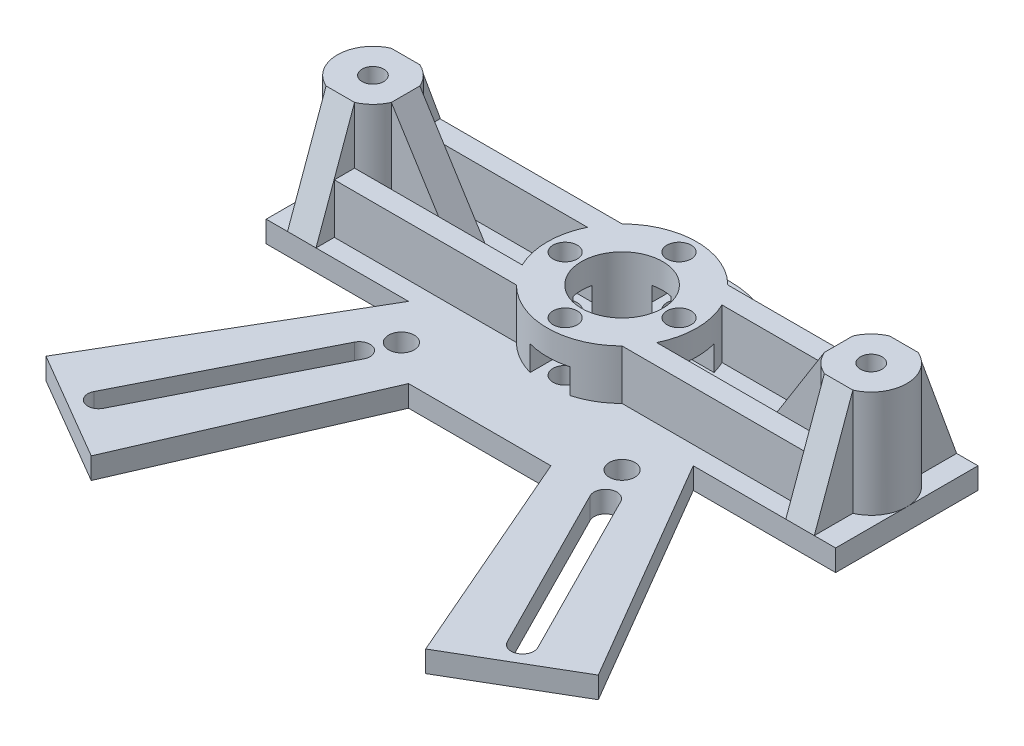
SolidWorks part; units mm, degrees
ref_plane "前视基准面" through (0, 0, 0) normal (0, 0, 1) x (1, 0, 0)
ref_plane "上视基准面" through (0, 0, 0) normal (0, 1, 0) x (1, 0, 0)
ref_plane "右视基准面" through (0, 0, 0) normal (1, 0, 0) x (0, 0, -1)
sketch "草图1" plane through (0, 0, 0) normal (0, 1, 0) x (1, 0, 0)
  line L0 (-35.0818, -10) -> (-40, -10)
  line L1 (-40, -10) -> (-40, 10)
  line L2 (-40, 10) -> (-11.1803, 10)
  line L3 (-9.9994, -20.0003) -> (10.0006, -20.0003)
  line L4 (40, 10) -> (40, -10)
  line L5 (40, -10) -> (20, -10)
  line L6 (-20, -10) -> (-38.7957, -42.1354)
  line L7 (10.0006, -20.0003) -> (23.4932, -51.0857)
  line L8 (20, -10) -> (38.796, -42.135)
  line L9 (-15.5, -15.5) -> (-31.1994, -46.5784) construction
  line L10 (15.5, -15.5) -> (31.1994, -46.5783) construction
  line L11 (-38.7957, -42.1354) -> (-23.4932, -51.0857)
  line L12 (-17.4886, -19.4366) -> (-29.776, -43.7606) construction
  line L13 (-16.1319, -20.122) -> (-28.4192, -44.4459)
  line L14 (-18.8453, -18.7513) -> (-31.1327, -43.0752)
  line L15 (17.824, -20.1595) -> (29.776, -43.7606) construction
  line L16 (19.2514, -19.4366) -> (31.2034, -43.0377)
  line L17 (16.3966, -20.8823) -> (28.3486, -44.4834)
  line L18 (11.1803, 10) -> (40, 10)
  line L19 (-35.0818, -10) -> (-20, -10)
  line L20 (-9.9994, -20.0003) -> (-23.4932, -51.0857)
  line L22 (23.4932, -51.0857) -> (38.796, -42.135)
  circle A0 centre (35, 0) radius 3.2
  circle A2 centre (-15.5, -15.5) radius 1.8
  circle A3 centre (15.5, -15.5) radius 1.8
  circle A4 centre (-35, 0) radius 3.2
  arc A6 (-16.1319, -20.122) -> (-18.8453, -18.7513) centre (-17.4886, -19.4366) ccw
  arc A7 (-31.1327, -43.0752) -> (-28.4192, -44.4459) centre (-29.776, -43.7606) ccw
  circle A8 centre (0, 0) radius 5.7
  circle A9 centre (-8, 0) radius 1.7
  circle A10 centre (0, 8) radius 1.7
  circle A11 centre (8, 0) radius 1.7
  circle A12 centre (0, -8) radius 1.7
  arc A13 (19.2514, -19.4366) -> (16.3966, -20.8823) centre (17.824, -20.1595) ccw
  arc A14 (28.3486, -44.4834) -> (31.2034, -43.0377) centre (29.776, -43.7606) ccw
  arc A17 (11.1803, 10) -> (-11.1803, 10) centre (0, 0) ccw
  point P34 (-33.1606, -34.0237)
  point P38 (-23.6323, -31.5986)
  point P43 (23.8, -31.96)
extrude "凸台-拉伸1" add sketch "草图1" along normal blind 3
sketch "草图2" plane through (0, 3, 0) normal (0, 1, 0) x (1, 0, 0)
  circle A0 centre (0, 0) radius 10.5
extrude "凸台-拉伸2" add sketch "草图2" along normal blind 7
sketch "草图4" plane through (0, 3, 0) normal (0, -1, 0) x (1, 0, 0)
  circle A1 centre (0, -8) radius 1.7
  circle A2 centre (-8, 0) radius 1.7
  circle A3 centre (8, 0) radius 1.7
  circle A4 centre (0, 8) radius 1.7
extrude "切除-拉伸1" cut sketch "草图4" against normal blind 7
sketch "草图5" plane through (0, 3, 0) normal (0, 1, 0) x (1, 0, 0)
  line L1 (-4.7668, 0) -> (-6.3834, 2.8)
  line L2 (-6.3834, 2.8) -> (-11.2332, 2.8)
  line L5 (-11.2332, -2.8) -> (-6.3834, -2.8)
  line L6 (-6.3834, -2.8) -> (-4.7668, 0)
  line L7 (4.7668, 0) -> (6.3834, -2.8)
  line L8 (6.3834, -2.8) -> (11.2332, -2.8)
  line L11 (11.2332, 2.8) -> (6.3834, 2.8)
  line L12 (6.3834, 2.8) -> (4.7668, 0)
  line L14 (-2.8, 11.2332) -> (-2.8, 6.3834)
  line L15 (-2.8, 6.3834) -> (0, 4.7668)
  line L16 (0, 4.7668) -> (2.8, 6.3834)
  line L17 (2.8, 6.3834) -> (2.8, 11.2332)
  line L19 (0, -4.7668) -> (-2.8, -6.3834)
  line L20 (-2.8, -6.3834) -> (-2.8, -11.2332)
  line L23 (2.8, -11.2332) -> (2.8, -6.3834)
  line L24 (2.8, -6.3834) -> (0, -4.7668)
  line L25 (-11.2332, 2.8) -> (-11.2332, -2.8)
  line L29 (-2.8, 11.2332) -> (2.8, 11.2332)
  line L32 (11.2332, 2.8) -> (11.2332, -2.8)
  line L35 (-2.8, -11.2332) -> (2.8, -11.2332)
  line L39 (-1.4, -10.4249) -> (0, -11.2332) [skipped]
  line L40 (1.4, -10.4249) -> (2.8, -9.6166) [skipped]
  line L41 (9.6166, -2.8) -> (10.4249, -1.4) [skipped]
  line L42 (11.2332, 0) -> (10.4249, 1.4) [skipped]
  line L43 (1.4, 10.4249) -> (0, 11.2332) [skipped]
  line L44 (0, 11.2332) -> (-1.4, 10.4249) [skipped]
  line L45 (-10.4249, -1.4) -> (-9.6166, -2.8) [skipped]
  line L46 (-9.6166, 2.8) -> (-10.4249, 1.4) [skipped]
extrude "切除-拉伸2" cut sketch "草图5" along normal blind 3.5
sketch "草图6" plane through (0, 3, 0) normal (0, -1, 0) x (1, 0, 0)
  circle A0 centre (0, 0) radius 5.7
extrude "切除-拉伸3" cut sketch "草图6" against normal blind 20
sketch "草图7" plane through (0, 3, 0) normal (0, 1, 0) x (1, 0, 0)
  circle A0 centre (-35, 0) radius 1.525
  circle A1 centre (-35, 0) radius 5
  circle A2 centre (35, 0) radius 1.525
  circle A3 centre (35, 0) radius 5
  dimension "D1" = 3.05
  dimension "D2" = 3.05
extrude "凸台-拉伸3" add sketch "草图7" along normal blind 15
sketch "草图8" plane through (0, 3, 0) normal (0, 1, 0) x (1, 0, 0)
  line L0 (-11.1803, 10) -> (-40, 10) construction
  line L1 (-31, -2) -> (-21, -2)
  line L2 (-31, -2) -> (-31, 2)
  line L3 (-31, 2) -> (-21, 2)
  line L4 (-21, -2) -> (-21, 2)
  line L5 (-33, 4) -> (-37, 4)
  line L6 (-33, 4) -> (-33, 10)
  line L7 (-33, 10) -> (-37, 10)
  line L8 (-37, 4) -> (-37, 10)
  line L9 (-40, -10) -> (-20, -10) construction
  line L10 (-37, -4) -> (-33, -4)
  line L11 (-37, -4) -> (-37, -10)
  line L12 (-37, -10) -> (-33, -10)
  line L13 (-33, -4) -> (-33, -10)
  line L14 (40, 10) -> (11.1803, 10) construction
  line L15 (31, 2) -> (21, 2)
  line L16 (31, 2) -> (31, -2)
  line L17 (31, -2) -> (21, -2)
  line L18 (21, 2) -> (21, -2)
  line L19 (33, 4) -> (37, 4)
  line L20 (33, 4) -> (33, 10)
  line L21 (33, 10) -> (37, 10)
  line L22 (37, 4) -> (37, 10)
  line L23 (20, -10) -> (40, -10) construction
  line L24 (33, -4) -> (37, -4)
  line L25 (33, -4) -> (33, -10)
  line L26 (33, -10) -> (37, -10)
  line L27 (37, -4) -> (37, -10)
extrude "凸台-拉伸4" add sketch "草图8" along normal blind 15
sketch "草图9" plane through (0, 0, 2) normal (0, 0, 1) x (1, 0, 0)
  line L0 (-30.4174, 18) -> (-21, 3)
  line L1 (-30.4174, 18) -> (-21, 18)
  line L2 (-30.4174, 18) -> (-21, 18) construction
  line L3 (-21, 18) -> (-21, 3)
  line L4 (21, 3) -> (30.4174, 18)
  line L5 (30.4174, 18) -> (21, 18)
  line L6 (21, 18) -> (21, 3)
extrude "切除-拉伸4" cut sketch "草图9" against normal blind 15
sketch "草图10" plane through (33, 0, 0) normal (-1, 0, 0) x (0, 0, 1)
  line L0 (-4.5826, 18) -> (-10, 3)
  line L1 (-10, 18) -> (-10, 3) construction
  line L2 (-10, 3) -> (-10, 18)
  line L3 (-10, 18) -> (-4.5826, 18) construction
  line L4 (-10, 18) -> (-4.5826, 18)
  line L5 (4.5826, 18) -> (10, 18)
  line L6 (10, 18) -> (10, 3)
  line L7 (4.5826, 3) -> (10, 3) construction
  line L8 (10, 18) -> (10, 3) construction
  line L9 (10, 3) -> (4.5826, 18)
extrude "切除-拉伸5" cut sketch "草图10" against normal blind 15
sketch "草图11" plane through (-33, 0, 0) normal (1, 0, 0) x (0, 0, -1)
  line L0 (-4.5826, 18) -> (-10, 3)
  line L1 (-10, 3) -> (-10, 18)
  line L2 (-10, 18) -> (-4.5826, 18)
  line L3 (4.5826, 18) -> (10, 3)
  line L4 (10, 3) -> (10, 18)
  line L5 (10, 18) -> (4.5826, 18)
extrude "切除-拉伸6" cut sketch "草图11" against normal blind 15
sketch "草图12" plane through (0, 3, 0) normal (0, 1, 0) x (1, 0, 0)
  line L1 (-33, -4.5826) -> (-7.4246, -4.5826)
  line L2 (-33, -4.5826) -> (-33, -7.4246)
  line L3 (-33, -7.4246) -> (-7.4246, -7.4246)
  line L4 (-7.4246, -4.5826) -> (-7.4246, -7.4246)
  line L5 (-33, 4.5826) -> (-7.4246, 4.5826)
  line L6 (-33, 4.5826) -> (-33, 7.4246)
  line L7 (-33, 7.4246) -> (-7.4246, 7.4246)
  line L8 (-7.4246, 4.5826) -> (-7.4246, 7.4246)
  line L9 (33, 4.5826) -> (7.4246, 4.5826)
  line L10 (33, 4.5826) -> (33, 7.4246)
  line L11 (33, 7.4246) -> (7.4246, 7.4246)
  line L12 (7.4246, 4.5826) -> (7.4246, 7.4246)
  line L13 (33, -4.5826) -> (7.4246, -4.5826)
  line L14 (33, -4.5826) -> (33, -7.4246)
  line L15 (33, -7.4246) -> (7.4246, -7.4246)
  line L16 (7.4246, -4.5826) -> (7.4246, -7.4246)
  arc A0 (-10.1198, -2.8) -> (-2.8, -10.1198) centre (0, 0) ccw construction
  arc A1 (-2.8, 10.1198) -> (-10.1198, 2.8) centre (0, 0) ccw construction
  arc A2 (10.1198, 2.8) -> (2.8, 10.1198) centre (0, 0) ccw construction
  arc A3 (2.8, -10.1198) -> (10.1198, -2.8) centre (0, 0) ccw construction
extrude "凸台-拉伸5" add sketch "草图12" along normal blind 7
